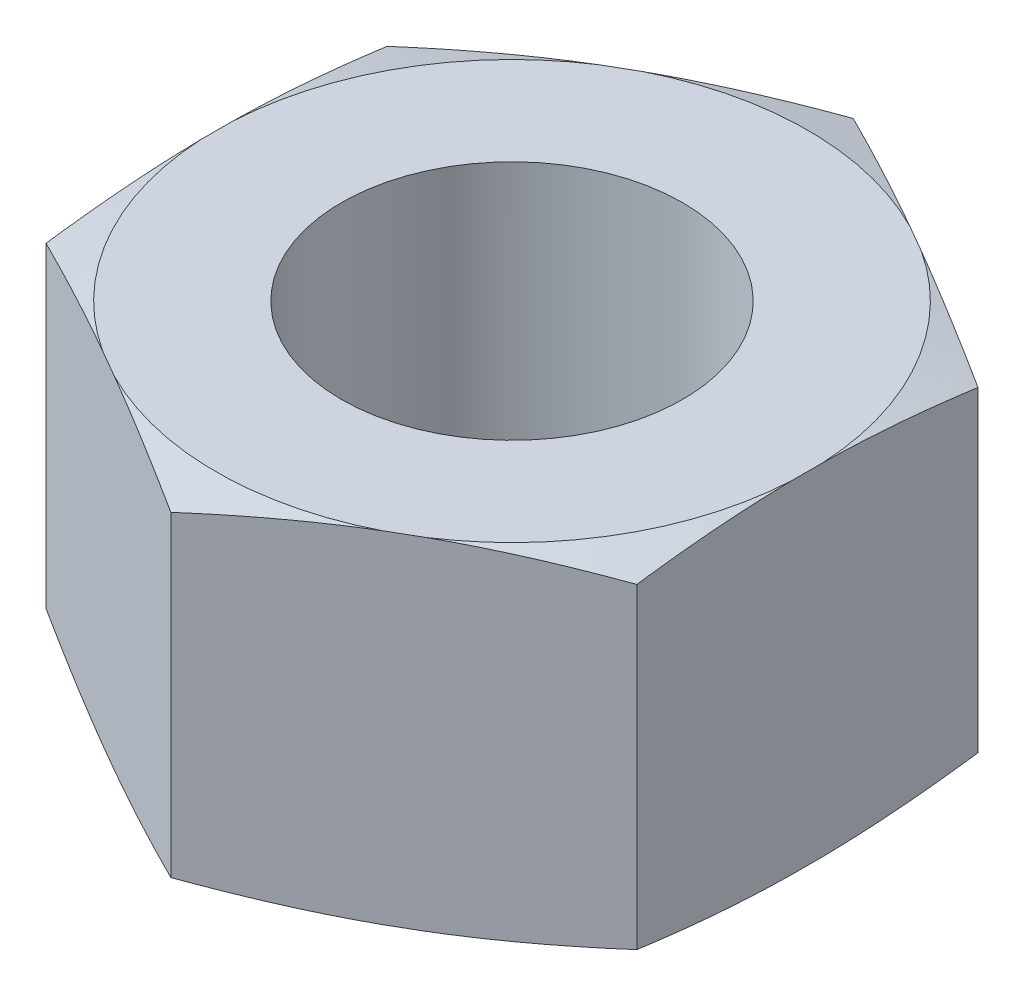
SolidWorks part; units mm, degrees
ref_plane "Front Plane" through (0, 0, 0) normal (0, 0, 1) x (1, 0, 0)
ref_plane "Top Plane" through (0, 0, 0) normal (0, 1, 0) x (1, 0, 0)
ref_plane "Right Plane" through (0, 0, 0) normal (1, 0, 0) x (0, 0, -1)
sketch "Sketch4" plane through (0, 0, 0) normal (0, 1, 0) x (1, 0, 0)
  line L1 (0, -16) -> (13.8564, -8)
  line L2 (13.8564, -8) -> (13.8564, 8)
  line L3 (13.8564, 8) -> (0, 16)
  line L4 (0, 16) -> (-13.8564, 8)
  line L5 (-13.8564, 8) -> (-13.8564, -8)
  line L6 (-13.8564, -8) -> (0, -16)
  circle A0 centre (0, 0) radius 13.8564 construction
  dimension "D1" = 32
extrude "Boss-Extrude2" add sketch "Sketch4" against normal blind 16
sketch "Sketch5" plane through (0, 0, 0) normal (0, 0, 1) x (1, 0, 0)
  line L0 (-13.8759, 0) -> (-18.013, 0)
  line L1 (17.5282, 0) -> (-17.5282, 0) construction
  line L2 (-18.013, 0) -> (-18.013, -1.1353)
  line L3 (-18.013, -1.1353) -> (-13.8759, 0)
  line L4 (0, 7.0324) -> (0, -18.307) construction
  line L5 (0, -17.6) -> (0, 17.6) construction
revolve "Cut-Revolve2" cut sketch "Sketch5" angle 360 about L4
sketch "Sketch9" plane through (0, -16, 0) normal (0, -1, 0) x (1, 0, 0)
  circle A0 centre (0, 0) radius 8
extrude "Cut-Extrude3" cut sketch "Sketch9" against normal blind 64 contours A0
ref_plane "Plane2" through (0, -8, 0) normal (0, 1, 0) x (1, 0, 0)
mirror "Mirror1" about plane through (0, -8, 0) normal (0, 1, 0) of "Cut-Revolve2"
